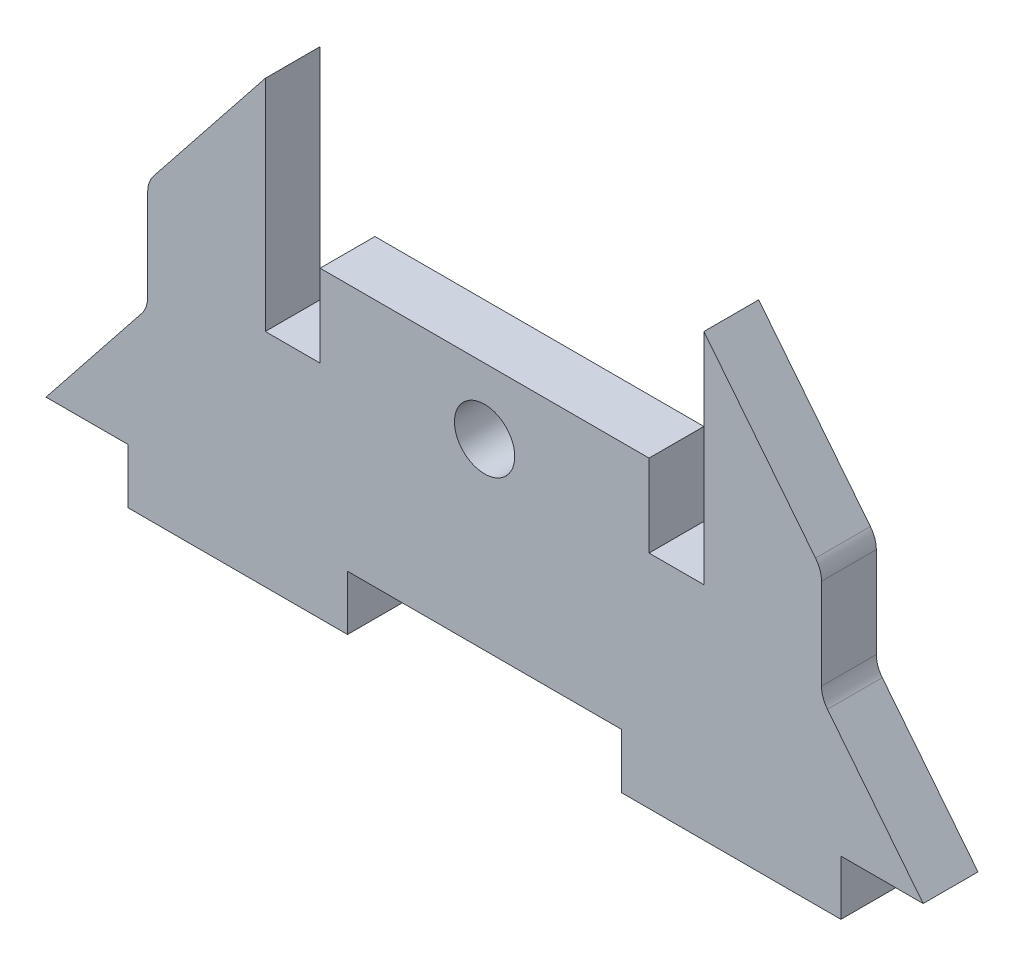
SolidWorks part; units mm, degrees
ref_plane "Front Plane" through (0, 0, 0) normal (0, 0, 1) x (1, 0, 0)
ref_plane "Top Plane" through (0, 0, 0) normal (0, 1, 0) x (1, 0, 0)
ref_plane "Right Plane" through (0, 0, 0) normal (1, 0, 0) x (0, 0, -1)
sketch "Sketch1" plane through (0, 0, 0) normal (0, 0, 1) x (1, 0, 0)
  line L0 (5, -6.674) -> (-5, -6.674)
  line L1 (-13, -8.674) -> (-13, -6.674)
  line L2 (-5, -8.674) -> (-5, -6.674)
  line L3 (-5, -8.674) -> (-13, -8.674)
  line L4 (8, 2.4) -> (8, -0.6)
  line L5 (8, -0.6) -> (6, -0.6)
  line L6 (6, -0.6) -> (6, 2.4)
  line L7 (6, 2.4) -> (-6, 2.4)
  line L8 (13, -6.674) -> (16, -6.674)
  line L9 (8, 7.4) -> (12.0737, 2.2765)
  line L10 (12.291, 1.6541) -> (12.291, -1.6601)
  line L11 (12.5083, -2.2824) -> (16, -6.674)
  line L12 (-13, -6.674) -> (-16, -6.674)
  line L13 (-12.5083, -2.2824) -> (-16, -6.674)
  line L14 (-12.291, 1.6541) -> (-12.291, -1.6601)
  line L15 (-8, 7.4) -> (-12.0737, 2.2765)
  line L16 (-8, 2.4) -> (-8, 7.4)
  line L17 (-8, 2.4) -> (-8, -0.6)
  line L18 (-8, -0.6) -> (-6, -0.6)
  line L19 (-6, -0.6) -> (-6, 2.4)
  line L28 (0, 14.3668) -> (0, -6.674) construction
  line L29 (0, -6.674) -> (25.1167, -6.674) construction
  line L31 (8, 2.4) -> (8, 7.4)
  line L33 (13, 1.7941) -> (13, -6.674) construction
  line L34 (5, -8.674) -> (13, -8.674)
  line L35 (5, -8.674) -> (5, -6.674)
  line L44 (13, -8.674) -> (13, -6.674)
  arc A0 (-12.5083, -2.2824) -> (-12.291, -1.6601) centre (-13.291, -1.6601) ccw
  arc A1 (-12.291, 1.6541) -> (-12.0737, 2.2765) centre (-11.291, 1.6541) cw
  arc A2 (12.291, -1.6601) -> (12.5083, -2.2824) centre (13.291, -1.6601) ccw
  arc A3 (12.0737, 2.2765) -> (12.291, 1.6541) centre (11.291, 1.6541) cw
  circle A5 centre (0, 0) radius 1.1
  point P20 (-12.291, -2.0092)
  point P23 (-12.291, 2.0032)
  point P26 (12.291, -2.0092)
  point P29 (12.291, 2.0032)
  dimension "D2" = 2
  dimension "D3" = 2.2
  dimension "D12" = 1
  dimension "D4" = 2.4
  dimension "D5" = 8
  dimension "D6" = 8
  dimension "D7" = 5
  dimension "D8" = 2
  dimension "D9" = 3
  dimension "D10" = 3
  dimension "D11" = 9.074
  dimension "D13" = 8
extrude "Boss-Extrude1" add sketch "Sketch1" along normal blind 2
